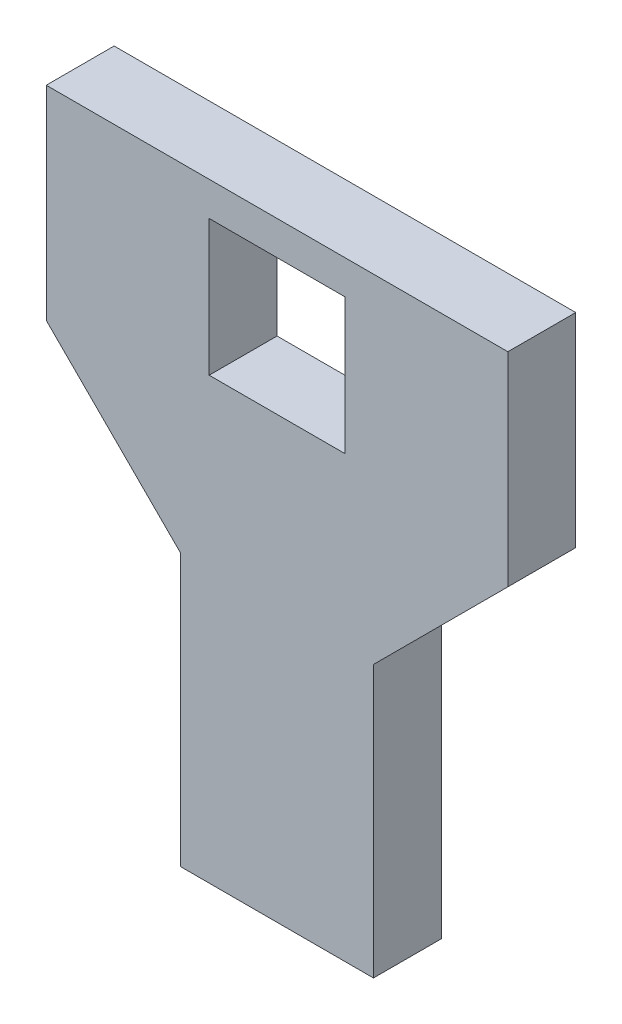
SolidWorks part; units mm, degrees
ref_plane "Alzado" through (0, 0, 0) normal (0, 0, 1) x (1, 0, 0)
ref_plane "Planta" through (0, 0, 0) normal (0, 1, 0) x (1, 0, 0)
ref_plane "Vista lateral" through (0, 0, 0) normal (1, 0, 0) x (0, 0, -1)
sketch "Croquis1" plane through (0, 0, 0) normal (0, 0, 1) x (1, 0, 0)
  line L8 (0, 0) -> (0, -37.3995) construction
  line L13 (-5, 5) -> (5, 5)
  line L19 (-5, 5) -> (-5, -5)
  line L20 (-5, -5) -> (5, -5)
  line L32 (5, 5) -> (5, -5)
  line L37 (-5, 5) -> (5, -5) construction
  line L38 (-5, -5) -> (5, 5) construction
  line L39 (-17, 7.5) -> (17, 7.5)
  line L40 (-17, 7.5) -> (-17, -7.5)
  line L41 (-17, -7.5) -> (17, -7.5)
  line L42 (17, 7.5) -> (17, -7.5)
  line L43 (-17, 7.5) -> (17, -7.5) construction
  line L44 (-17, -7.5) -> (17, 7.5) construction
  line L45 (-17, -7.5) -> (-7.1005, -17.3995)
  line L46 (-7.1005, -17.3995) -> (-7.1005, -37.3995)
  line L47 (-7.1005, -37.3995) -> (7.1005, -37.3995)
  line L48 (7.1005, -17.3995) -> (7.1005, -37.3995)
  line L49 (17, -7.5) -> (7.1005, -17.3995)
  point P0 (0, 0)
  point P5 (0, 0)
  dimension "D1" = 10
  dimension "D2" = 34
  dimension "D3" = 15
  dimension "D6" = 20
  dimension "D4" = 45
  dimension "D5" = 14
extrude "Saliente-Extruir1" add sketch "Croquis1" along normal blind 5 contours L42 L39 L40 L41 L13 L32 L20 L19 | L49 L41 L45 L46 L47 L48
